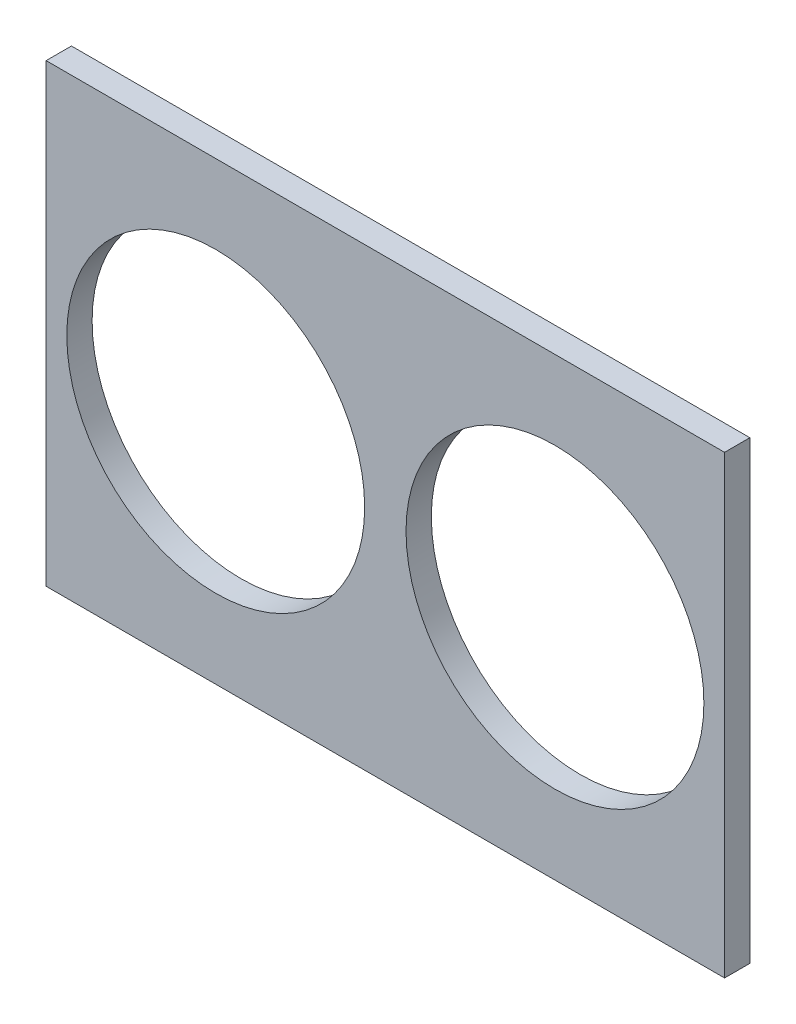
SolidWorks part; units mm, degrees
ref_plane "Front Plane" through (0, 0, 0) normal (0, 0, 1) x (1, 0, 0)
ref_plane "Top Plane" through (0, 0, 0) normal (0, 1, 0) x (1, 0, 0)
ref_plane "Right Plane" through (0, 0, 0) normal (1, 0, 0) x (0, 0, -1)
sketch "Sketch1" plane through (0, 0, 0) normal (0, 0, 1) x (1, 0, 0)
  line L0 (0, 0) -> (37.8511, 0)
  line L1 (37.8511, 0) -> (37.8511, -25.4)
  line L2 (0, 0) -> (0, -25.4)
  line L3 (0, -25.4) -> (37.8511, -25.4)
  line L4 (18.9255, 0) -> (18.9255, -25.4) construction
  line L6 (0, -12.7) -> (18.9255, -12.7) construction
  line L7 (18.9255, -12.7) -> (37.8511, -12.7) construction
  circle A0 centre (9.4628, -12.7) radius 8.309
  circle A1 centre (28.3883, -12.7) radius 8.309
extrude "Boss-Extrude1" add sketch "Sketch1" against normal blind 1.4122
